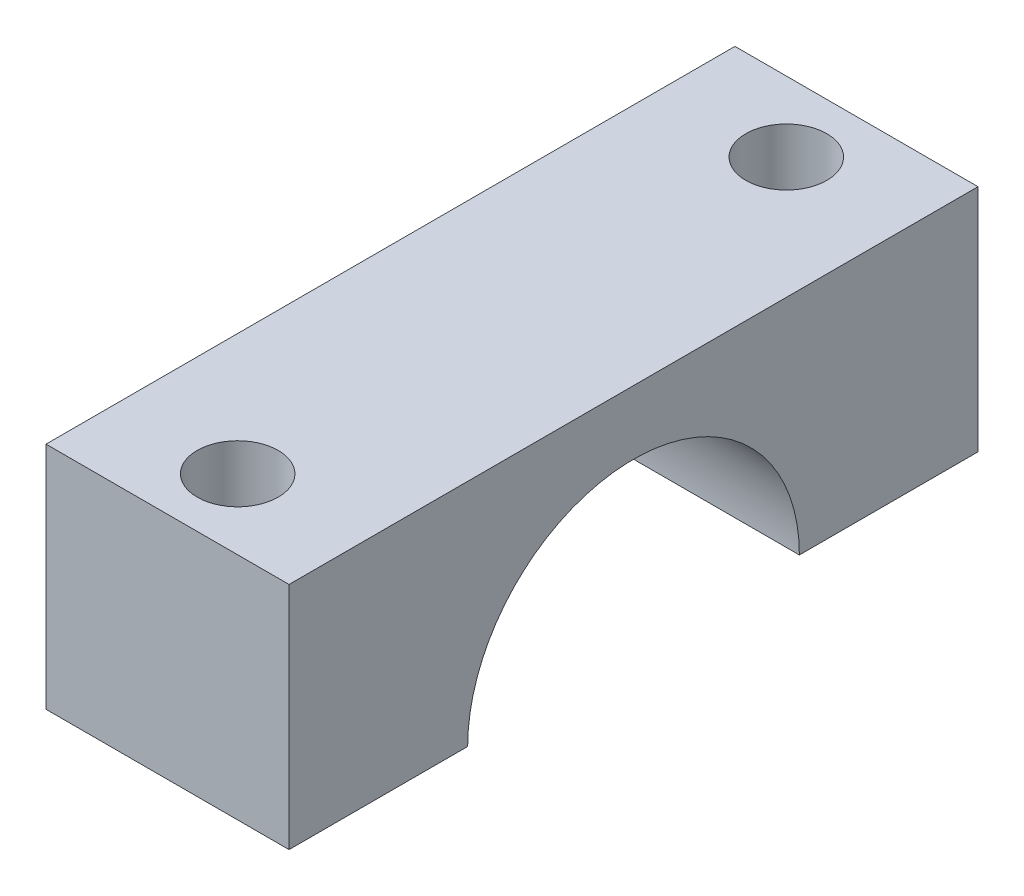
SolidWorks part; units mm, degrees
ref_plane "Front Plane" through (0, 0, 0) normal (0, 0, 1) x (1, 0, 0)
ref_plane "Top Plane" through (0, 0, 0) normal (0, 1, 0) x (1, 0, 0)
ref_plane "Right Plane" through (0, 0, 0) normal (1, 0, 0) x (0, 0, -1)
sketch "Sketch1" plane through (0, 0, 0) normal (1, 0, 0) x (0, 0, -1)
  line L0 (-6.5, 0) -> (-13.5, 0)
  line L1 (13.5, 9) -> (-13.5, 9)
  line L2 (13.5, 9) -> (13.5, 0)
  line L3 (13.5, 0) -> (6.5, 0)
  line L4 (-13.5, 9) -> (-13.5, 0)
  arc A0 (6.5, 0) -> (-6.5, 0) centre (0, 0) ccw
  dimension "D1" = 13
  dimension "D2" = 0
  dimension "D3" = 27
  dimension "D4" = 13.5
  dimension "D5" = 9
extrude "Boss-Extrude1" add sketch "Sketch1" along normal blind 9.525
sketch "Sketch2" plane through (0, 9, 0) normal (0, 1, 0) x (1, 0, 0)
  line L0 (9.525, -13.5) -> (0, -13.5) construction
  line L1 (9.525, 13.5) -> (9.525, -13.5) construction
  line L2 (9.525, 13.5) -> (0, 13.5) construction
  circle A0 centre (4.7625, -10.75) radius 1.5875
  circle A1 centre (4.7625, 10.75) radius 1.5875
  dimension "D1" = 3.175
  dimension "D4" = 3.175
  dimension "D2" = 2.75
  dimension "D3" = 4.7625
  dimension "D5" = 2.75
  dimension "D6" = 4.7625
extrude "Cut-Extrude1" cut sketch "Sketch2" against normal through all
equation "\"D4@Sketch1\"=\"D3@Sketch1\"/2"
equation "\"D5@Sketch2\"=\"D2@Sketch2\""
equation "\"D4@Sketch2\"=\"D1@Sketch2\""
equation "\"D6@Sketch2\"=\"D3@Sketch2\""
